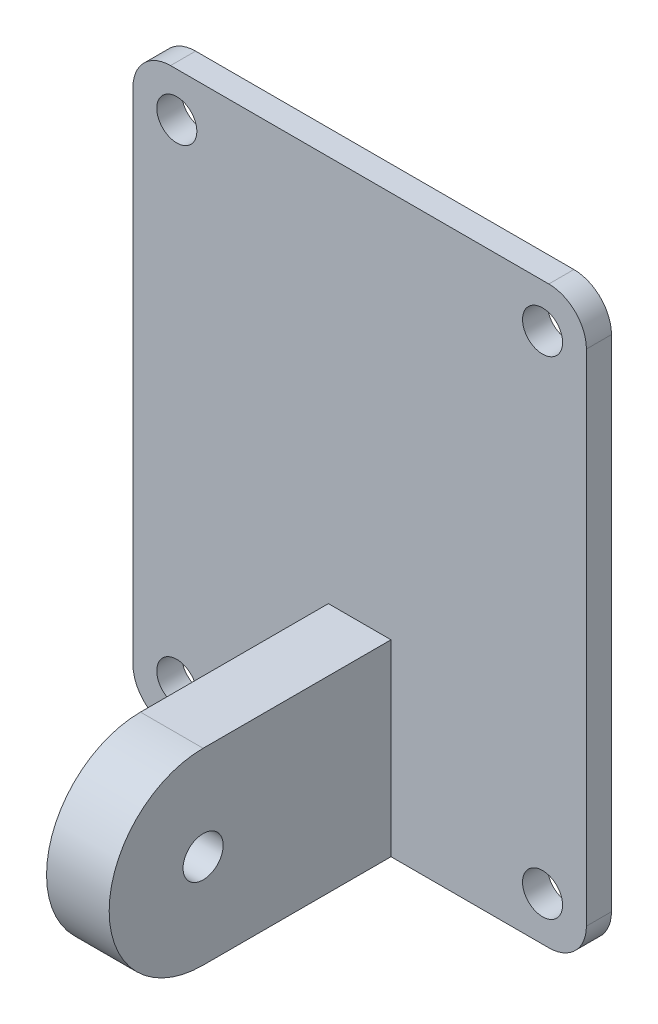
SolidWorks part; units mm, degrees
ref_plane "前视基准面" through (0, 0, 0) normal (0, 0, 1) x (1, 0, 0)
ref_plane "上视基准面" through (0, 0, 0) normal (0, 1, 0) x (1, 0, 0)
ref_plane "右视基准面" through (0, 0, 0) normal (1, 0, 0) x (0, 0, -1)
sketch "Model" plane through (0, 0, 0) normal (0, 0, 1) x (1, 0, 0)
  line L0 (312.8824, 324.0411) -> (343.0824, 324.0411)
  line L1 (346.0824, 321.0411) -> (346.0824, 281.1411)
  line L2 (312.8824, 278.1411) -> (343.0824, 278.1411)
  line L3 (309.8824, 321.0411) -> (309.8824, 281.1411)
  circle A0 centre (313.3824, 320.5411) radius 1.6
  circle A1 centre (313.3824, 281.6411) radius 1.6
  circle A2 centre (342.5824, 320.5411) radius 1.6
  circle A3 centre (342.5824, 281.6411) radius 1.6
  arc A4 (312.8824, 324.0411) -> (309.8824, 321.0411) centre (312.8824, 321.0411) ccw
  arc A5 (346.0824, 321.0411) -> (343.0824, 324.0411) centre (343.0824, 321.0411) ccw
  arc A6 (343.0824, 278.1411) -> (346.0824, 281.1411) centre (343.0824, 281.1411) ccw
  arc A7 (309.8824, 281.1411) -> (312.8824, 278.1411) centre (312.8824, 281.1411) ccw
extrude "凸台-拉伸1" add sketch "Model" along normal blind 2
sketch "草图2" plane through (0, 0, 2) normal (0, 0, 1) x (1, 0, 0)
  line L0 (327.9824, 324.0411) -> (327.9824, 278.1411) construction
  line L1 (343.0824, 324.0411) -> (312.8824, 324.0411) construction
  line L2 (312.8824, 278.1411) -> (343.0824, 278.1411) construction
  line L3 (309.8824, 301.0911) -> (346.0824, 301.0911) construction
  line L4 (309.8824, 321.0411) -> (309.8824, 281.1411) construction
  line L5 (346.0824, 281.1411) -> (346.0824, 321.0411) construction
  line L6 (325.4824, 293.1411) -> (325.4824, 278.1411)
  line L7 (325.4824, 278.1411) -> (330.4824, 278.1411)
  line L8 (330.4824, 278.1411) -> (330.4824, 293.1411)
  line L9 (330.4824, 293.1411) -> (325.4824, 293.1411)
  dimension "D1" = 2.5
  dimension "D2" = 0
  dimension "D3" = 15
extrude "凸台-拉伸2" add sketch "草图2" along normal blind 15
sketch "草图3" plane through (325.4824, 0, 0) normal (-1, 0, 0) x (0, 0, 1)
  line L0 (17, 293.1411) -> (17, 278.1411)
  arc A0 (17, 278.1411) -> (17, 293.1411) centre (17, 285.6411) ccw
  dimension "D1" = 15
extrude "凸台-拉伸3" add sketch "草图3" against normal blind 5
sketch "草图4" plane through (325.4824, 0, 0) normal (-1, 0, 0) x (0, 0, 1)
  line L0 (2, 293.1411) -> (2, 278.1411) construction
  line L1 (17, 293.1411) -> (2, 293.1411) construction
  circle A0 centre (17, 285.6411) radius 1.6
  dimension "D1" = 3.2
  dimension "D2" = 15
  dimension "D3" = 7.5
extrude "切除-拉伸1" cut sketch "草图4" against normal blind 5
